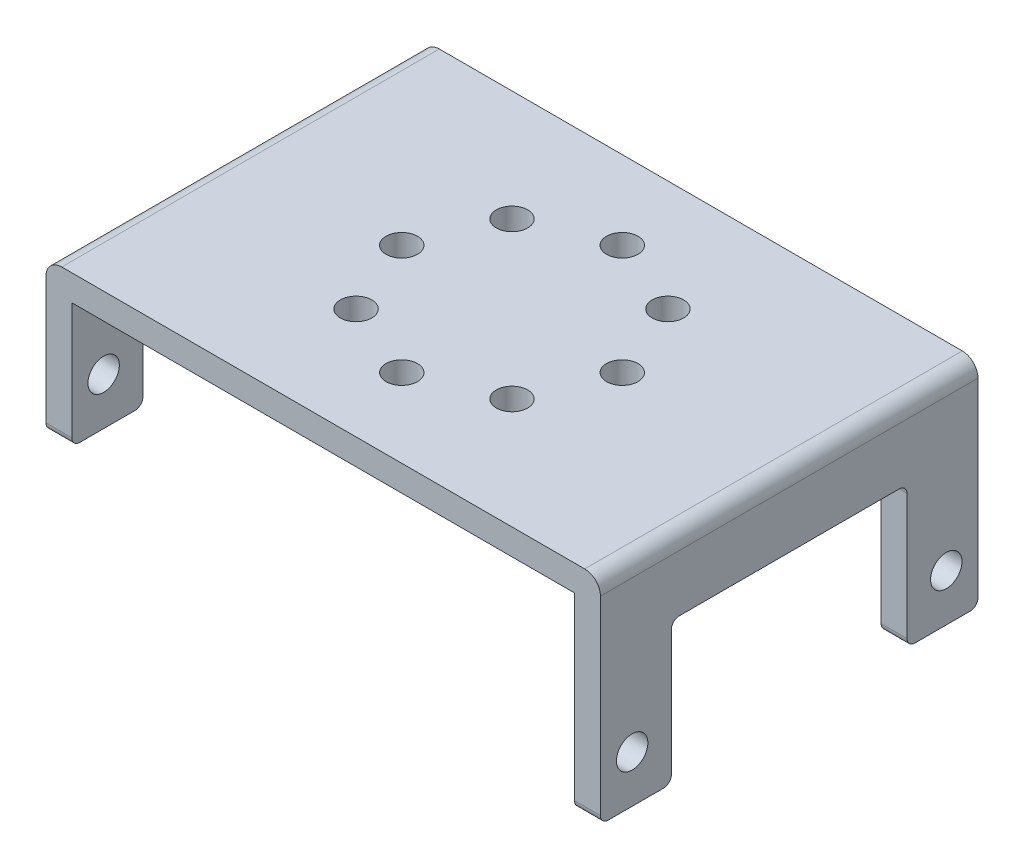
SolidWorks part; units mm, degrees
ref_plane "Front Plane" through (0, 0, 0) normal (0, 0, 1) x (1, 0, 0)
ref_plane "Top Plane" through (0, 0, 0) normal (0, 1, 0) x (1, 0, 0)
ref_plane "Right Plane" through (0, 0, 0) normal (1, 0, 0) x (0, 0, -1)
sketch "Sketch1" plane through (0, 0, 0) normal (0, 1, 0) x (1, 0, 0)
  line L1 (-17.65, 12.02) -> (17.65, 12.02)
  line L2 (-17.65, 12.02) -> (-17.65, -12.02)
  line L3 (-17.65, -12.02) -> (17.65, -12.02)
  line L4 (17.65, 12.02) -> (17.65, -12.02)
  line L5 (-17.65, 12.02) -> (17.65, -12.02) construction
  line L6 (-17.65, -12.02) -> (17.65, 12.02) construction
  circle A0 centre (0, 7.02) radius 1
  circle A1 centre (4.9639, 4.9639) radius 1
  circle A2 centre (7.02, 0) radius 1
  circle A3 centre (4.9639, -4.9639) radius 1
  circle A4 centre (0, -7.02) radius 1
  circle A5 centre (-4.9639, -4.9639) radius 1
  circle A6 centre (-7.02, 0) radius 1
  circle A7 centre (-4.9639, 4.9639) radius 1
  point P0 (0, 0)
  point P24 (0, 0)
  dimension "D3" = 2
  dimension "D4" = 7.02
  dimension "D1" = 35.3
  dimension "D2" = 24.04
  dimension "D5" = 8
  dimension "D6" = 10.63
extrude "Boss-Extrude1" add sketch "Sketch1" along normal blind 1.65
sketch "Sketch2" plane through (17.65, 0, 0) normal (1, 0, 0) x (0, 0, -1)
  line L0 (12.02, 1.65) -> (12.02, 0) construction
  line L1 (12.02, 1.65) -> (12.02, 0)
  line L2 (7.5, -11.95) -> (12.02, -11.95)
  line L3 (-12.02, 0) -> (12.02, 0)
  line L4 (-12.02, 0) -> (-12.02, -11.95)
  line L5 (-12.02, -11.95) -> (-7.5, -11.95)
  line L6 (12.02, 0) -> (12.02, -11.95)
  line L7 (-7.5, -2.95) -> (7.5, -2.95)
  line L8 (-7.5, -2.95) -> (-7.5, -11.95)
  line L10 (7.5, -2.95) -> (7.5, -11.95)
  line L11 (0, 16.4113) -> (0, -19.9375) construction
  circle A0 centre (10, -8.95) radius 1
  circle A1 centre (-10, -8.95) radius 1
  point P5 (0, -11.95)
  line M10 (-12.02, 0) -> (12.02, 0)
  dimension "D4" = 2
  dimension "D1" = 11.95
  dimension "D2" = 9
  dimension "D3" = 15
  dimension "D5" = 2.5
  dimension "D6" = 7.5
  dimension "D7" = 3
extrude "Boss-Extrude2" add sketch "Sketch2" against normal blind 1.65 contours L11 L4 L5 L8 L7 A1 M10 | L3 L11 L7 L10 L2 L6 A0
sketch "Sketch3" plane through (-17.65, 0, 0) normal (-1, 0, 0) x (0, 0, 1)
  line L0 (12.02, 1.65) -> (12.02, 0) construction
  line L1 (12.02, 1.65) -> (12.02, 0)
  line L2 (7.5, -7.95) -> (12.02, -7.95)
  line L3 (-12.02, 0) -> (12.02, 0)
  line L4 (-12.02, 0) -> (-12.02, -7.95)
  line L5 (-12.02, -7.95) -> (-7.5, -7.95)
  line L6 (12.02, 0) -> (12.02, -7.95)
  line L7 (-7.5, -2.95) -> (7.5, -2.95)
  line L8 (-7.5, -2.95) -> (-7.5, -7.95)
  line L10 (7.5, -2.95) -> (7.5, -7.95)
  line L11 (0, 3.5412) -> (0, -14.6742) construction
  circle A0 centre (10, -4.95) radius 1
  circle A1 centre (-10, -4.95) radius 1
  point P5 (0, -9.26)
  line M12 (-12.02, 0) -> (12.02, 0)
  dimension "D4" = 2
  dimension "D1" = 7.95
  dimension "D2" = 15
  dimension "D3" = 5
  dimension "D5" = 2.5
  dimension "D6" = 7.5
  dimension "D7" = 3
extrude "Boss-Extrude3" add sketch "Sketch3" against normal blind 1.65 contours L11 L4 L5 L8 L7 A1 M12 | L3 L11 L7 L10 L2 L6 A0
fillet "Fillet1" radius 1 1 edges at (17.65, 1.65, 0)
fillet "Fillet2" radius 1 1 edges at (-17.65, 1.65, 0)
fillet "Fillet3" radius 0.5 12 edges at (-16.825, -7.95, 12.02) (-16.825, -7.95, 7.5) (-16.825, -2.95, 7.5) (-16.825, -2.95, -7.5) (-16.825, -7.95, -7.5) (-16.825, -7.95, -12.02) (16.825, -11.95, -12.02) (16.825, -11.95, -7.5) (16.825, -2.95, -7.5) (16.825, -2.95, 7.5) (16.825, -11.95, 7.5) (16.825, -11.95, 12.02)
